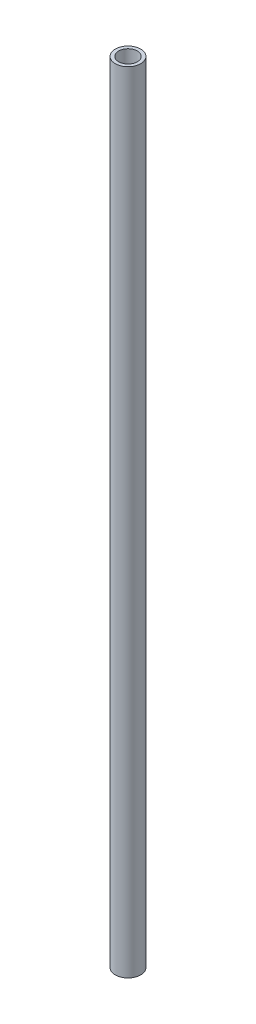
SolidWorks part; units mm, degrees
ref_plane "Front" through (0, 0, 0) normal (0, 0, 1) x (1, 0, 0)
ref_plane "Top" through (0, 0, 0) normal (0, 1, 0) x (1, 0, 0)
ref_plane "Right" through (0, 0, 0) normal (1, 0, 0) x (0, 0, -1)
sketch "Sketch1" plane through (0, 0, 0) normal (0, 1, 0) x (1, 0, 0)
  circle A0 centre (0, 0) radius 3.5052
  circle A1 centre (0, 0) radius 4.7498
extrude "Boss-Extrude1" add sketch "Sketch1" along normal blind 295.275
